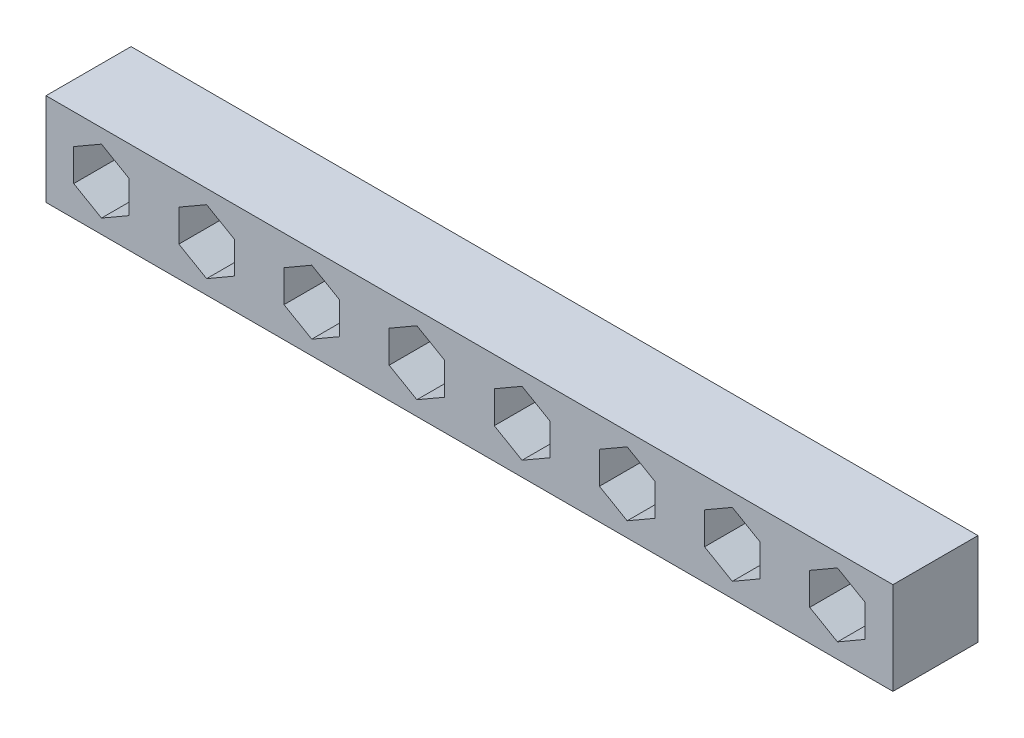
SolidWorks part; units mm, degrees
ref_plane "Front Plane" through (0, 0, 0) normal (0, 0, 1) x (1, 0, 0)
ref_plane "Top Plane" through (0, 0, 0) normal (0, 1, 0) x (1, 0, 0)
ref_plane "Right Plane" through (0, 0, 0) normal (1, 0, 0) x (0, 0, -1)
sketch "Sketch1" plane through (0, 0, 0) normal (0, 0, 1) x (1, 0, 0)
  line L1 (0, 0) -> (229, 0)
  line L2 (0, 0) -> (0, 25)
  line L3 (0, 25) -> (229, 25)
  line L4 (229, 0) -> (229, 25)
  dimension "D1" = 229
  dimension "D2" = 25
extrude "Boss-Extrude1" add sketch "Sketch1" along normal blind 23
sketch "Sketch2" plane through (0, 0, 23) normal (0, 0, 1) x (1, 0, 0)
  line L0 (0, 12.5) -> (26.3457, 12.5) construction
  line L1 (0, 25) -> (0, 0) construction
  line L2 (43.4286, 21.1979) -> (35.9286, 16.8678)
  line L3 (15, 3.8397) -> (22.5, 8.1699)
  line L4 (22.5, 8.1699) -> (22.5, 16.8301)
  line L5 (22.5, 16.8301) -> (15, 21.1603)
  line L6 (15, 21.1603) -> (7.5, 16.8301)
  line L7 (7.5, 16.8301) -> (7.5, 8.1699)
  line L8 (7.5, 8.1699) -> (15, 3.8397)
  line L9 (50.9286, 16.8678) -> (43.4286, 21.1979)
  line L10 (50.9286, 8.2076) -> (50.9286, 16.8678)
  line L11 (43.4286, 3.8774) -> (50.9286, 8.2076)
  line L12 (35.9286, 8.2076) -> (43.4286, 3.8774)
  line L13 (35.9286, 16.8678) -> (35.9286, 8.2076)
  line L14 (71.8571, 21.2356) -> (64.3571, 16.9055)
  line L15 (79.3571, 16.9055) -> (71.8571, 21.2356)
  line L16 (79.3571, 8.2453) -> (79.3571, 16.9055)
  line L17 (71.8571, 3.9151) -> (79.3571, 8.2453)
  line L18 (64.3571, 8.2453) -> (71.8571, 3.9151)
  line L19 (64.3571, 16.9055) -> (64.3571, 8.2453)
  line L20 (100.2857, 21.2733) -> (92.7857, 16.9432)
  line L21 (107.7857, 16.9432) -> (100.2857, 21.2733)
  line L22 (107.7857, 8.2829) -> (107.7857, 16.9432)
  line L23 (100.2857, 3.9528) -> (107.7857, 8.2829)
  line L24 (92.7857, 8.2829) -> (100.2857, 3.9528)
  line L25 (92.7857, 16.9432) -> (92.7857, 8.2829)
  line L26 (128.7143, 21.311) -> (121.2143, 16.9809)
  line L27 (136.2143, 16.9809) -> (128.7143, 21.311)
  line L28 (136.2143, 8.3206) -> (136.2143, 16.9809)
  line L29 (128.7143, 3.9905) -> (136.2143, 8.3206)
  line L30 (121.2143, 8.3206) -> (128.7143, 3.9905)
  line L31 (121.2143, 16.9809) -> (121.2143, 8.3206)
  line L32 (157.1429, 21.3487) -> (149.6429, 17.0186)
  line L33 (164.6429, 17.0186) -> (157.1429, 21.3487)
  line L34 (164.6429, 8.3583) -> (164.6429, 17.0186)
  line L35 (157.1429, 4.0282) -> (164.6429, 8.3583)
  line L36 (149.6429, 8.3583) -> (157.1429, 4.0282)
  line L37 (149.6429, 17.0186) -> (149.6429, 8.3583)
  line L38 (185.5714, 21.3864) -> (178.0714, 17.0563)
  line L39 (193.0714, 17.0563) -> (185.5714, 21.3864)
  line L40 (193.0714, 8.396) -> (193.0714, 17.0563)
  line L41 (185.5714, 4.0659) -> (193.0714, 8.396)
  line L42 (178.0714, 8.396) -> (185.5714, 4.0659)
  line L43 (178.0714, 17.0563) -> (178.0714, 8.396)
  line L44 (214, 21.4241) -> (206.5, 17.094)
  line L45 (221.5, 17.094) -> (214, 21.4241)
  line L46 (221.5, 8.4337) -> (221.5, 17.094)
  line L47 (214, 4.1036) -> (221.5, 8.4337)
  line L48 (206.5, 8.4337) -> (214, 4.1036)
  line L49 (206.5, 17.094) -> (206.5, 8.4337)
  line L50 (229, 0) -> (229, 25) construction
  circle A0 centre (15, 12.5) radius 7.5 construction
  point P5 (221.5, 12.5)
  dimension "D1" = 15
  dimension "D2" = 8
  dimension "D3" = 7.5
  dimension "D4" = 7.5
extrude "Cut-Extrude1" cut sketch "Sketch2" against normal blind 23
